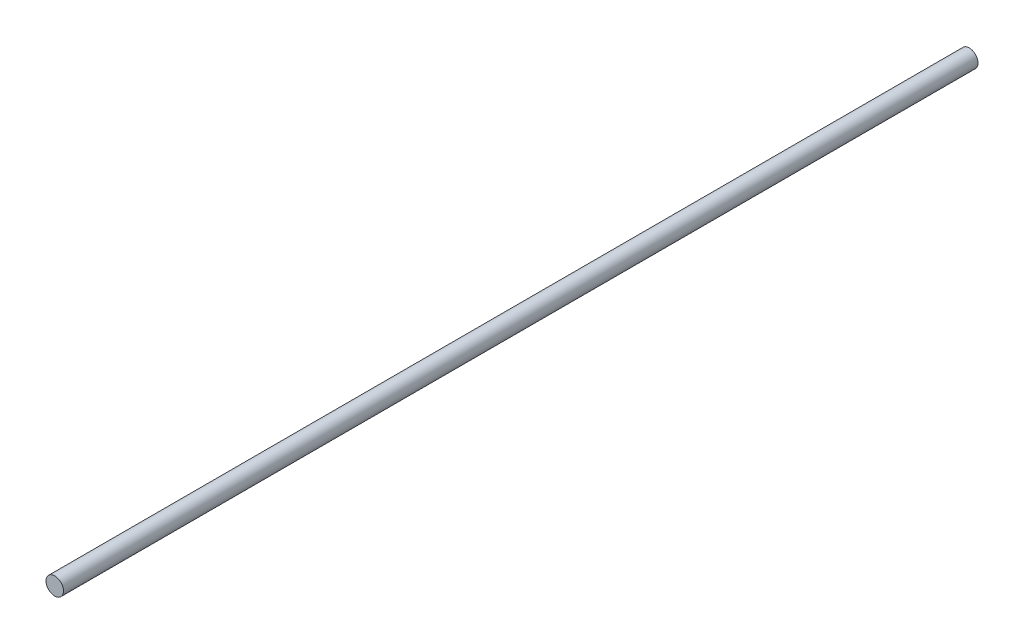
SolidWorks part; units mm, degrees
material "Обычная углеродистая сталь"
ref_plane "Спереди" through (0, 0, 0) normal (0, 0, 1) x (1, 0, 0)
ref_plane "Сверху" through (0, 0, 0) normal (0, 1, 0) x (1, 0, 0)
ref_plane "Справа" through (0, 0, 0) normal (1, 0, 0) x (0, 0, -1)
sketch "Эскиз1" plane through (0, 0, 0) normal (0, 1, 0) x (1, 0, 0)
  line L0 (3.25, 0) -> (0, 0)
  line L1 (0, 0) -> (0, -340)
  line L2 (0, -340) -> (3.25, -340)
  line L3 (3.25, -340) -> (3.25, 0)
  line L4 (0, 0) -> (0, -340) construction
revolve "Повернуть1" add sketch "Эскиз1" angle 360 about L4
